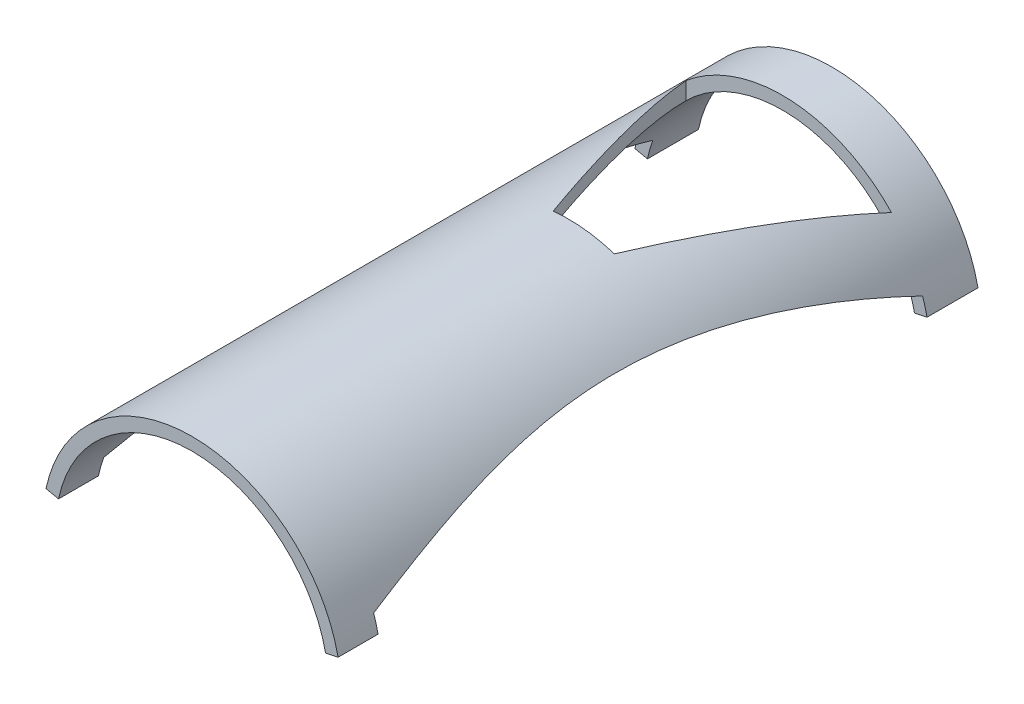
SolidWorks part; units mm, degrees
ref_plane "Alzado" through (0, 0, 0) normal (0, 0, 1) x (1, 0, 0)
ref_plane "Planta" through (0, 0, 0) normal (0, 1, 0) x (1, 0, 0)
ref_plane "Vista lateral" through (0, 0, 0) normal (1, 0, 0) x (0, 0, -1)
sketch "Croquis1" plane through (0, 0, 0) normal (0, 0, 1) x (1, 0, 0)
  line L0 (0, 0) -> (-34.2352, 7.2769) construction
  line L1 (-34.2352, 7.2769) -> (-31.3007, 6.6532)
  line L2 (0, 0) -> (0, 35) construction
  line L3 (0, 0) -> (34.2352, 7.2769) construction
  line L4 (31.3007, 6.6532) -> (34.2352, 7.2769)
  arc A0 (34.2352, 7.2769) -> (-34.2352, 7.2769) centre (0, 0) ccw
  arc A1 (31.3007, 6.6532) -> (-31.3007, 6.6532) centre (0, 0) ccw
  dimension "D1" = 70
  dimension "D2" = 3
extrude "Saliente-Extruir1" add sketch "Croquis1" along normal blind 150
sketch "Croquis2" plane through (0, 0, 0) normal (0, 1, 0) x (1, 0, 0)
  line L0 (-22.7088, -11.5547) -> (25.4976, -11.5547)
  line L1 (25.4976, -11.5547) -> (10.7568, -61.7532)
  line L2 (10.7568, -61.7532) -> (-3.5856, -61.7532)
  line L3 (-3.5856, -61.7532) -> (-22.7088, -11.5547)
extrude "Cortar-Extruir1" cut sketch "Croquis2" along normal through all
sketch "Croquis3" plane through (0, 0, 0) normal (1, 0, 0) x (0, 0, -1)
  line L0 (-11.9531, 11.0658) -> (-11.9531, 0)
  line L1 (-11.9531, 0) -> (-140.6365, 0)
  line L2 (-140.6365, 0) -> (-140.6365, 11.0658)
  arc A0 (-11.9531, 11.0658) -> (-140.6365, 11.0658) centre (-76.2948, -144.3326) ccw
extrude "Cortar-Extruir2" cut sketch "Croquis3" against normal mid plane 150
